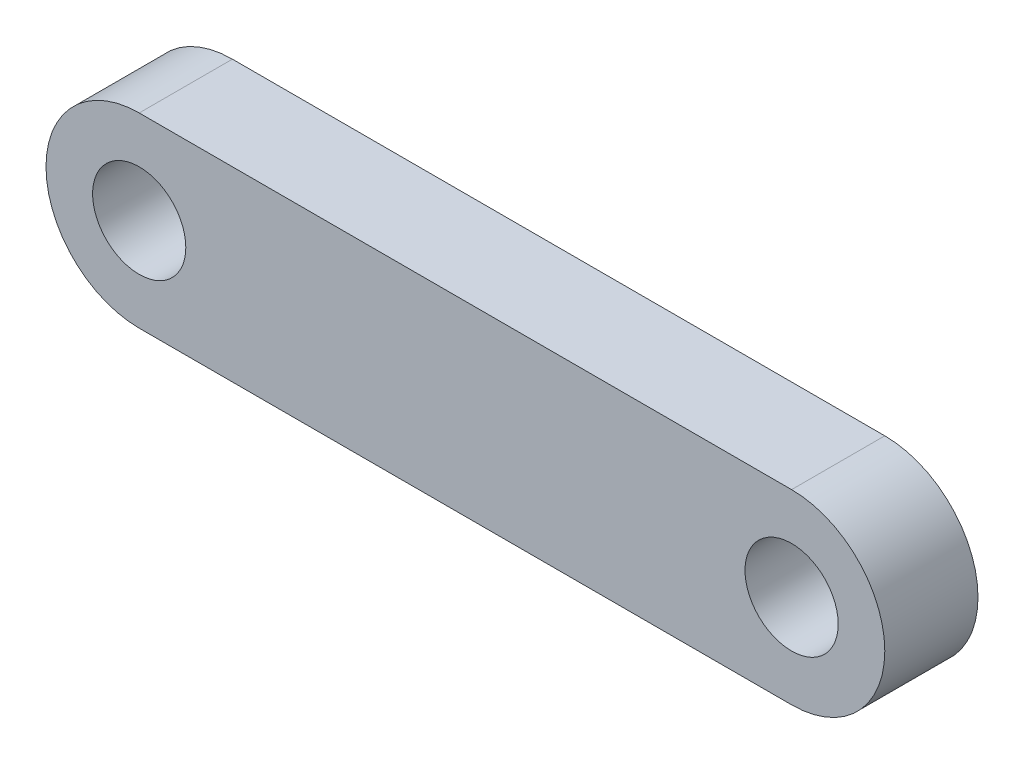
SolidWorks part; units mm, degrees
material "普通碳钢"
ref_plane "前视基准面" through (0, 0, 0) normal (0, 0, 1) x (1, 0, 0)
ref_plane "上视基准面" through (0, 0, 0) normal (0, 1, 0) x (1, 0, 0)
ref_plane "右视基准面" through (0, 0, 0) normal (1, 0, 0) x (0, 0, -1)
sketch "草图1" plane through (0, 0, 0) normal (0, 0, 1) x (1, 0, 0)
  line L0 (0, 0) -> (70, 0) construction
  line L1 (0, -10) -> (70, -10)
  line L2 (0, 10) -> (70, 10)
  arc A0 (0, 10) -> (0, -10) centre (0, 0) ccw
  arc A1 (70, 10) -> (70, -10) centre (70, 0) cw
  dimension "D3" = 70
  dimension "D1" = 10
  dimension "D2" = 10
extrude "凸台-拉伸1" add sketch "草图1" along normal blind 10
sketch "草图2" plane through (0, 0, 10) normal (0, 0, 1) x (1, 0, 0)
  circle A0 centre (0, 0) radius 5
  dimension "D1" = 10
extrude "切除-拉伸1" cut sketch "草图2" against normal blind 10
sketch "草图3" plane through (0, 0, 10) normal (0, 0, 1) x (1, 0, 0)
  circle A0 centre (70, 0) radius 5
  dimension "D1" = 10
extrude "切除-拉伸2" cut sketch "草图3" against normal blind 10
